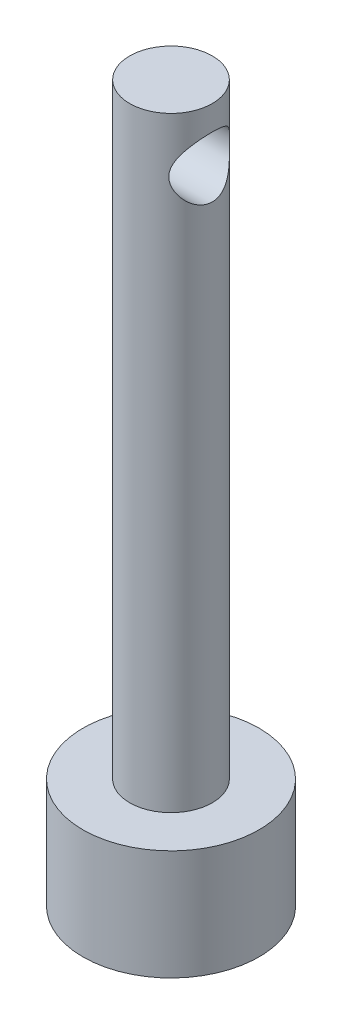
SolidWorks part; units mm, degrees
ref_plane "Front Plane" through (0, 0, 0) normal (0, 0, 1) x (1, 0, 0)
ref_plane "Top Plane" through (0, 0, 0) normal (0, 1, 0) x (1, 0, 0)
ref_plane "Right Plane" through (0, 0, 0) normal (1, 0, 0) x (0, 0, -1)
sketch "Sketch2" plane through (0, 0, 0) normal (0, 1, 0) x (1, 0, 0)
  circle A0 centre (0, 0) radius 3.1
  dimension "D1" = 6.2
sketch "Sketch3" plane through (0, 0, 0) normal (0, 1, 0) x (1, 0, 0)
  circle A0 centre (0, 0) radius 1.6
  dimension "D1" = 3.2
extrude "Boss-Extrude1" add sketch "Sketch3" along normal blind 2 contours A0
ref_plane "Plane1" through (0, 2, 0) normal (0, 1, 0) x (1, 0, 0)
sketch "Sketch4" plane through (0, 2, 0) normal (0, 1, 0) x (1, 0, 0)
  circle A0 centre (0, 0) radius 0.75
  dimension "D1" = 1.5
extrude "Boss-Extrude2" add sketch "Sketch4" along normal blind 11
sketch "Sketch5" plane through (0, 0, 0) normal (1, 0, 0) x (0, 0, -1)
  circle A0 centre (0, 12.0025) radius 0.55
  dimension "D1" = 1.1
extrude "Cut-Extrude1" cut sketch "Sketch5" against normal through all both and the other way through all
